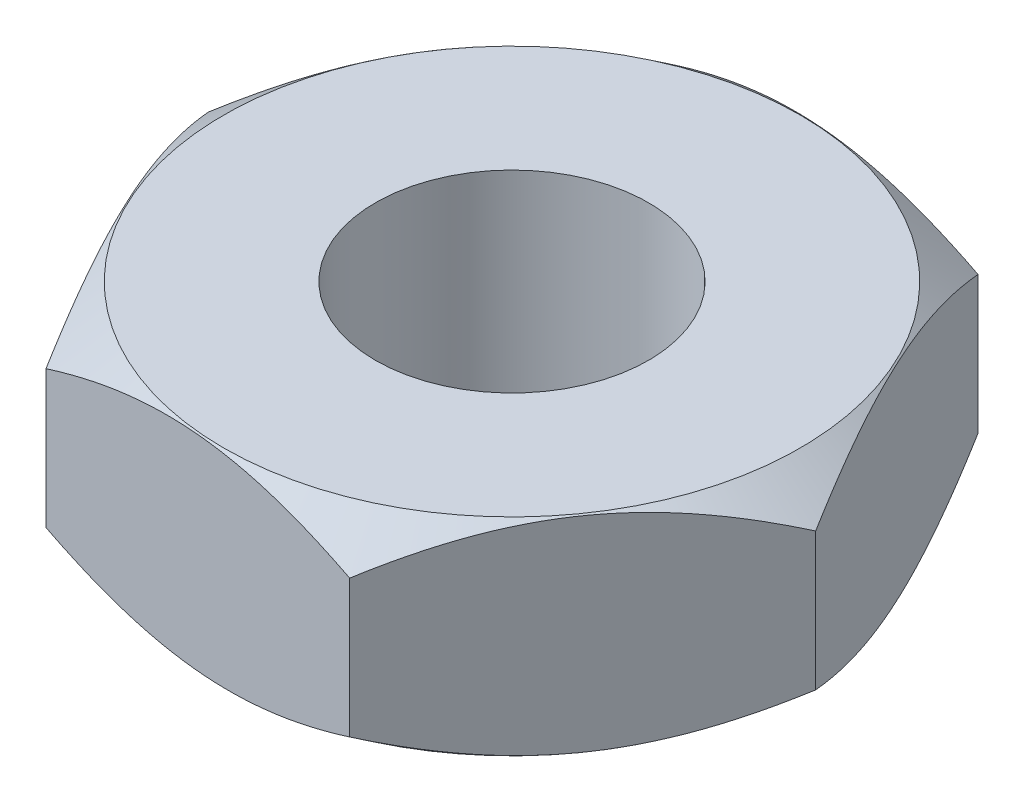
SolidWorks part; units mm, degrees
material "AISI 1015 Steel, Cold Drawn (SS)"
ref_plane "Front Plane" through (0, 0, 0) normal (0, 0, 1) x (1, 0, 0)
ref_plane "Top Plane" through (0, 0, 0) normal (0, 1, 0) x (1, 0, 0)
ref_plane "Right Plane" through (0, 0, 0) normal (1, 0, 0) x (0, 0, -1)
sketch "Sketch1" plane through (0, 0, 0) normal (0, 1, 0) x (1, 0, 0)
  line L1 (8.0513, -0.714) -> (4.644, 6.6157)
  line L2 (4.644, 6.6157) -> (-3.4073, 7.3296)
  line L3 (-3.4073, 7.3296) -> (-8.0513, 0.714)
  line L4 (-8.0513, 0.714) -> (-4.644, -6.6157)
  line L5 (-4.644, -6.6157) -> (3.4073, -7.3296)
  line L6 (3.4073, -7.3296) -> (8.0513, -0.714)
  circle A1 centre (0, 0) radius 3.3
  circle A2 centre (0, 0) radius 7 construction
  dimension "D1" = 14
  dimension "D2" = 6.6
extrude "Boss-Extrude1" add sketch "Sketch1" along normal mid plane 5
cosmetic thread "Cosmetic Thread1"
sketch "Sketch2" plane through (0, 0, 0) normal (0, 0, 1) x (1, 0, 0)
  line L0 (6.3, 3) -> (8.3, 3)
  line L1 (8.3, 3) -> (8.3, 1.5)
  line L2 (0, 3.5724) -> (0, -3.539) construction
  spline S0 degree 1 poles (6.3, 3) (8.3, 1.5) knots 0 0 1 1
  dimension "D1" = 2
  dimension "D2" = 1.5
  dimension "D3" = 1.5
  dimension "D4" = 6.3
revolve "Cut-Revolve1" cut sketch "Sketch2" angle 360 about L2
mirror "Mirror1" about plane through (0, 0, 0) normal (0, 1, 0) of "Cut-Revolve1"
